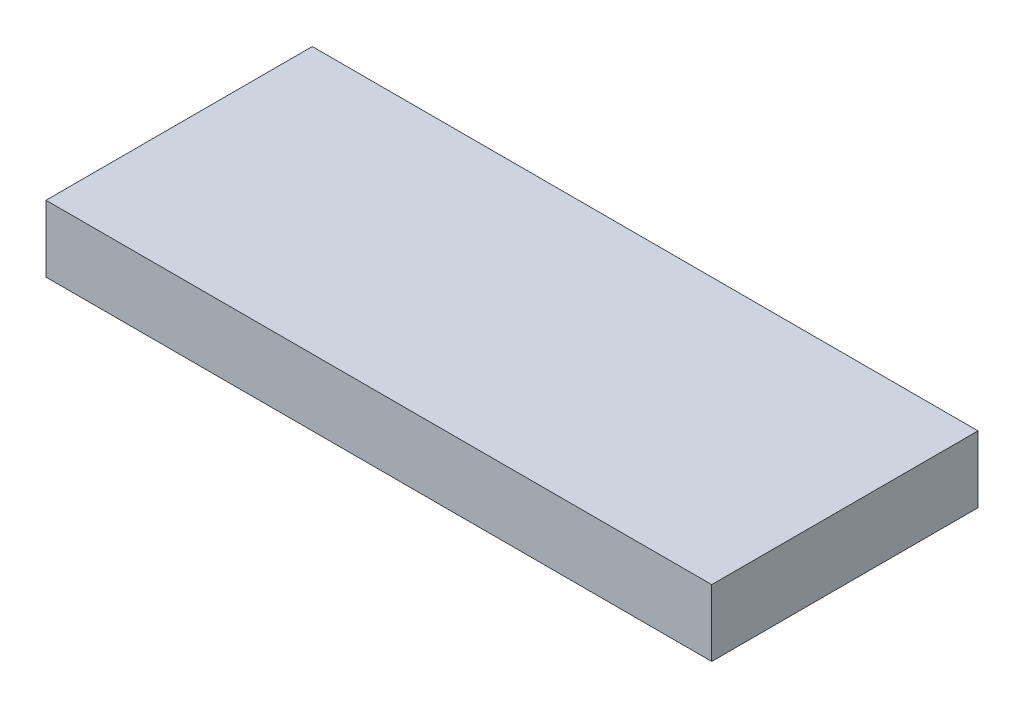
SolidWorks part; units mm, degrees
material "Pine"
ref_plane "Alzado" through (0, 0, 0) normal (0, 0, 1) x (1, 0, 0)
ref_plane "Planta" through (0, 0, 0) normal (0, 1, 0) x (1, 0, 0)
ref_plane "Vista lateral" through (0, 0, 0) normal (1, 0, 0) x (0, 0, -1)
sketch "Sketch1" plane through (0, 0, 0) normal (0, 1, 0) x (1, 0, 0)
  line L1 (-152.4, -50.8) -> (152.4, -50.8)
  line L2 (-152.4, -50.8) -> (-152.4, 50.8)
  line L3 (-152.4, 50.8) -> (152.4, 50.8)
  line L4 (152.4, -50.8) -> (152.4, 50.8)
  line L5 (-152.4, -50.8) -> (152.4, 50.8) construction
  line L6 (-152.4, 50.8) -> (152.4, -50.8) construction
  point P0 (0, 0)
  dimension "D1" = 101.6
  dimension "D2" = 304.8
extrude "Boss-Extrude1" add sketch "Sketch1" along normal blind 25.4
sketch "Sketch2" plane through (0, 25.4, 0) normal (0, 1, 0) x (1, 0, 0)
  line L1 (-152.4, -50.8) -> (-101.6, -50.8)
  line L2 (-152.4, -50.8) -> (-152.4, 50.8)
  line L3 (-152.4, 50.8) -> (-101.6, 50.8)
  line L4 (-101.6, -50.8) -> (-101.6, 50.8)
  line L5 (-152.4, 50.8) -> (-152.4, -50.8) construction
  point P4 (-152.4, 0)
  point P7 (-152.4, 0)
  dimension "D1" = 101.6
  dimension "D2" = 50.8
extrude "Cut-Extrude1" cut sketch "Sketch2" against normal up to surface (25.4 mm away) up to face at (0, 0, 0)
